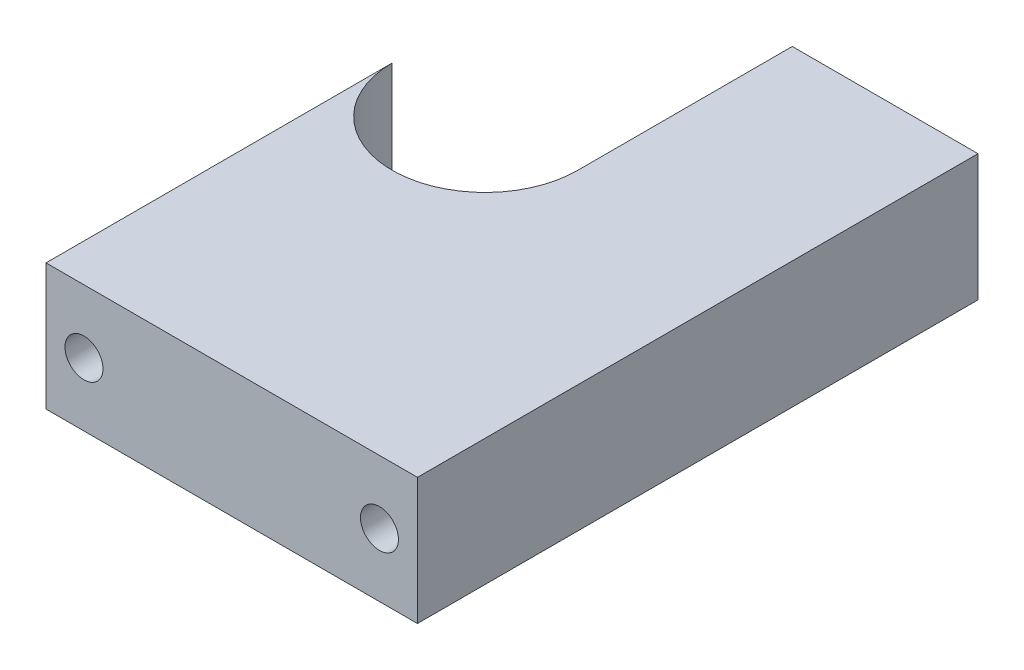
SolidWorks part; units mm, degrees
material "6061 Alloy"
ref_plane "Front" through (0, 0, 0) normal (0, 0, 1) x (1, 0, 0)
ref_plane "Top" through (0, 0, 0) normal (0, 1, 0) x (1, 0, 0)
ref_plane "Right" through (0, 0, 0) normal (1, 0, 0) x (0, 0, -1)
sketch "Sketch1" plane through (0, 0, 0) normal (0, 1, 0) x (1, 0, 0)
  line L0 (0, 0) -> (0, 41)
  line L1 (0, -50) -> (0, 50) construction
  line L4 (44, 41) -> (44, 0)
  line L5 (44, 0) -> (0, 0)
  line L8 (22, 41) -> (22, 66.4)
  line L9 (22, 66.4) -> (44, 66.4)
  line L10 (44, 66.4) -> (44, 41)
  arc A0 (22, 41) -> (0, 41) centre (11, 41) cw
  dimension "D1" = 44
  dimension "D2" = 22
  dimension "D3" = 25.4
  dimension "D4" = 41
extrude "Boss-Extrude1" add sketch "Sketch1" along normal blind 15
ref_plane "Plane1" through (0, 0, -12.7) normal (0, 0, -1) x (-1, 0, 0)
hole_wizard "M4 Clearance Hole5" positions "Sketch10" profile "Sketch11" hole size "M4" standard "ANSI Metric"
sketch "Sketch10" plane through (0, 0, -12.7) normal (0, 0, -1) x (-1, 0, 0)
  line L0 (-4.5, 15) -> (-4.5, 0) construction
  line L2 (50, 0) -> (-50, 0) construction
  line L5 (-39.5, 15) -> (-39.5, 0) construction
  line L8 (-39.5, 7.5) -> (-44, 7.5) construction
  line L11 (-4.5, 7.5) -> (0, 7.5) construction
  line L12 (0, 50) -> (0, -50) construction
  line L13 (-44, 15) -> (-44, 0) construction
  line L15 (-44, 15) -> (-22, 15) construction
  line L17 (0, 15) -> (-22, 15) construction
  point P0 (-39.5, 7.5)
  point P2 (-4.5, 7.5)
  point P52 (0, 0)
  point P53 (0, 0)
  point P56 (0, 0)
  point P57 (0, 0)
  point P58 (0, 0)
  point P59 (0, 0)
  point P60 (0, 0)
  point P61 (0, 0)
  point P62 (0, 0)
  point P63 (0, 0)
  dimension "D1" = 35
sketch "Sketch11" plane through (39.5, 7.5, -12.7) normal (1, 0, 0) x (0, 1, 0)
  line L0 (0, 0) -> (0, 12.7)
  line L1 (0, 12.7) -> (2.25, 12.7)
  line L2 (2.25, 12.7) -> (2.25, 0)
  line L5 (2.25, 0) -> (0, 0)
  line L11 (0, -6.35) -> (0, 107.95) construction
  dimension "Thru Hole Dia." = 4.5
  dimension "Thru Hole Depth" = 12.7
hole_wizard "Ø6.0mm Dowel Hole1" positions "Sketch12" profile "Sketch13" hole size "Ø6.0" standard "ANSI Metric"
sketch "Sketch12" plane through (0, 0, -12.7) normal (0, 0, -1) x (-1, 0, 0)
  line L0 (-44, 7.5) -> (-39.5, 7.5) construction
  line L3 (0, 7.5) -> (-4.5, 7.5) construction
  line L4 (0, 50) -> (0, -50) construction
  line L5 (-44, 15) -> (-44, 0) construction
  point P0 (-39.5, 7.5)
  point P2 (-4.5, 7.5)
  dimension "D1" = 35
sketch "Sketch13" plane through (39.5, 7.5, -12.7) normal (1, 0, 0) x (0, -1, 0)
  line L0 (0, 0) -> (0, 53.7)
  line L1 (0, 53.7) -> (3.75, 53.7)
  line L2 (3.75, 53.7) -> (3.75, 0)
  line L5 (3.75, 0) -> (0, 0)
  line L11 (0, -6.35) -> (0, 107.95) construction
  dimension "Thru Hole Dia." = 7.5
  dimension "Thru Hole Depth" = 53.7
